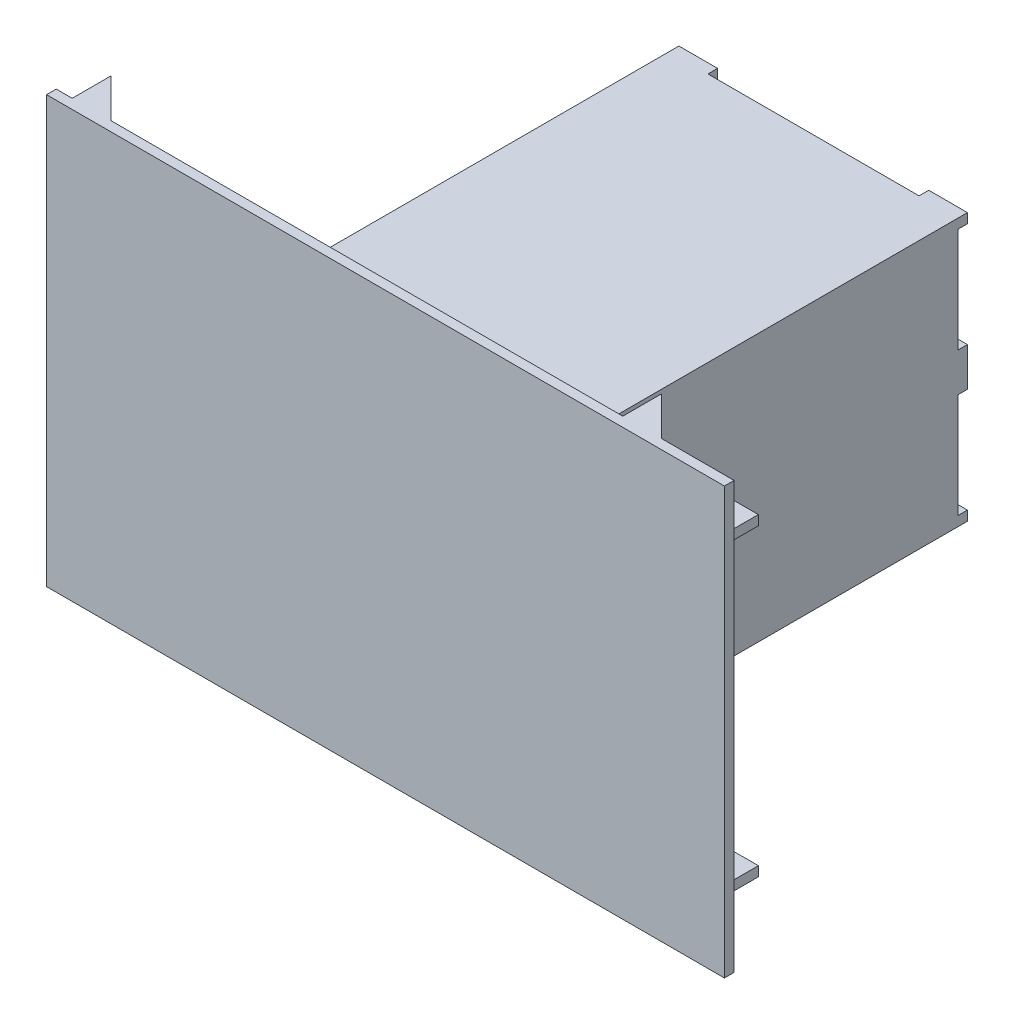
SolidWorks part; units mm, degrees
ref_plane "前视基准面" through (0, 0, 0) normal (0, 0, 1) x (1, 0, 0)
ref_plane "上视基准面" through (0, 0, 0) normal (0, 1, 0) x (1, 0, 0)
ref_plane "右视基准面" through (0, 0, 0) normal (1, 0, 0) x (0, 0, -1)
other "Configuration Table"
sketch "草图1" plane through (0, 0, 0) normal (0, 0, 1) x (1, 0, 0)
  line L0 (-60.5909, 0) -> (14.201, 0) construction
  line L1 (0, 25.976) -> (0, -21.0056) construction
  line L2 (66.5, -61) -> (4, -61)
  line L3 (-74.5, -69) -> (74.5, -69)
  line L4 (-74.5, -69) -> (-74.5, 69)
  line L5 (-74.5, 69) -> (74.5, 69)
  line L6 (74.5, -69) -> (74.5, 69)
  line L7 (-74.5, -69) -> (74.5, 69) construction
  line L8 (-74.5, 69) -> (74.5, -69) construction
  line L9 (-66.5, 61) -> (-4, 61)
  line L10 (-66.5, 61) -> (-66.5, -61)
  line L11 (-66.5, -61) -> (-4, -61)
  line L12 (-4, 61) -> (-4, -61)
  line L13 (4, 61) -> (4, -61)
  line L14 (66.5, 61) -> (4, 61)
  line L15 (66.5, 61) -> (66.5, -61)
  point P4 (0, 0)
  dimension "D1" = 149
  dimension "D2" = 138
  dimension "D3" = 8
  dimension "D4" = 8
  dimension "D5" = 8
extrude "凸台-拉伸1" add sketch "草图1" along normal blind 216
sketch "草图2" plane through (0, 0, 0) normal (0, 0, -1) x (-1, 0, 0)
  line L5 (74.5, 69) -> (74.5, -69) construction
  line L6 (74.5, 10) -> (69.5, 10)
  line L7 (74.5, 10) -> (74.5, -10)
  line L8 (74.5, -10) -> (69.5, -10)
  line L9 (69.5, 10) -> (69.5, -10)
  line L10 (-88.8421, 0) -> (129.204, 0) construction
  line L11 (0, 87.2221) -> (0, -106.4348) construction
  line L16 (-74.5, -10) -> (-69.5, -10)
  line L17 (-69.5, 10) -> (-69.5, -10)
  line L18 (-74.5, 10) -> (-69.5, 10)
  line L19 (-74.5, 10) -> (-74.5, -10)
  line L20 (74.5, 64) -> (54.5, 64)
  line L21 (-74.5, 69) -> (-54.5, 69)
  line L22 (-74.5, 69) -> (-74.5, 64)
  line L23 (-74.5, 64) -> (-54.5, 64)
  line L24 (-54.5, 69) -> (-54.5, 64)
  line L25 (54.5, 69) -> (54.5, 64)
  line L26 (74.5, 69) -> (54.5, 69)
  line L27 (74.5, 69) -> (74.5, 64)
  line L28 (74.5, -69) -> (74.5, -64)
  line L29 (74.5, -69) -> (54.5, -69)
  line L30 (54.5, -69) -> (54.5, -64)
  line L31 (74.5, -64) -> (54.5, -64)
  line L32 (-74.5, -64) -> (-54.5, -64)
  line L33 (-54.5, -69) -> (-54.5, -64)
  line L34 (-74.5, -69) -> (-54.5, -69)
  line L35 (-74.5, -69) -> (-74.5, -64)
  dimension "D1" = 5
  dimension "D2" = 5
  dimension "D3" = 20
  dimension "D4" = 20
extrude "凸台-拉伸2" add sketch "草图2" along normal blind 5
sketch "草图3" plane through (0, 0, 216) normal (0, 0, 1) x (1, 0, 0)
  line L5 (-175, -110) -> (175, -110)
  line L6 (-175, -110) -> (-175, 110)
  line L7 (-175, 110) -> (175, 110)
  line L8 (175, -110) -> (175, 110)
  line L9 (-175, -110) -> (175, 110) construction
  line L10 (-175, 110) -> (175, -110) construction
  point P0 (0, 0)
  dimension "D1" = 350
  dimension "D2" = 220
extrude "凸台-拉伸3" add sketch "草图3" along normal blind 5
sketch "草图5" plane through (0, 69, 0) normal (0, 1, 0) x (1, 0, 0)
  line L0 (-146.7541, -216) -> (-166.7541, -196)
  line L1 (175, -216) -> (-175, -216) construction
  line L2 (-166.7541, -196) -> (-166.7541, -216)
  line L3 (-166.7541, -216) -> (-146.7541, -216)
  line L4 (117.5459, -216) -> (137.5459, -216)
  line L5 (137.5459, -216) -> (117.5459, -196)
  line L6 (117.5459, -196) -> (117.5459, -216)
  line L7 (-166.7541, -216) -> (117.5459, -216) construction
  dimension "D1" = 45
  dimension "D2" = 20
  dimension "D3" = 2
  dimension "D4" = 284.3
extrude "凸台-拉伸4" add sketch "草图5" along normal blind 29 from offset 12
sketch "草图6" plane through (0, 81, 0) normal (0, -1, 0) x (1, 0, 0)
  line L0 (117.5459, 216) -> (167.5459, 216)
  line L1 (-166.7541, 216) -> (-116.7541, 216)
  line L2 (-166.7541, 216) -> (-166.7541, 196)
  line L3 (-166.7541, 196) -> (-116.7541, 196)
  line L4 (-116.7541, 216) -> (-116.7541, 196)
  line L5 (117.5459, 216) -> (117.5459, 196)
  line L6 (117.5459, 196) -> (167.5459, 196)
  line L7 (167.5459, 216) -> (167.5459, 196)
  line L8 (-166.7541, 216) -> (117.5459, 216) construction
  dimension "D1" = 50
  dimension "D3" = 284.3
  dimension "D2" = 2
extrude "凸台-拉伸5" add sketch "草图6" along normal blind 5
mirror "镜向1" about plane through (0, 0, 0) normal (0, 1, 0) of "凸台-拉伸5", "凸台-拉伸4"
